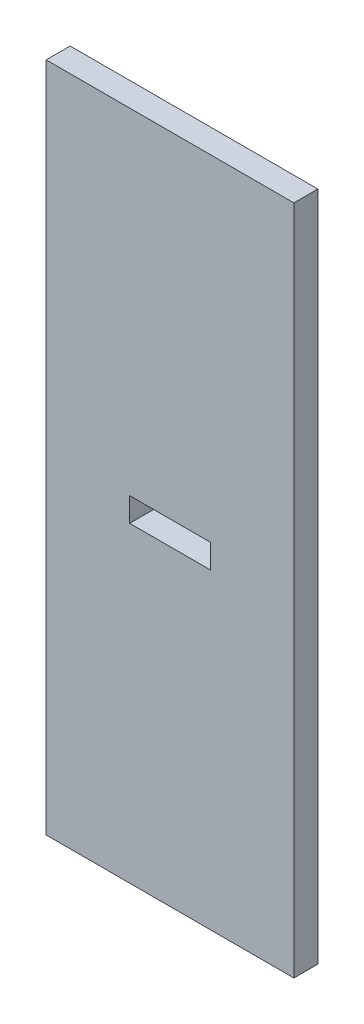
SolidWorks part; units mm, degrees
ref_plane "Plan de face" through (0, 0, 0) normal (0, 0, 1) x (1, 0, 0)
ref_plane "Plan de dessus" through (0, 0, 0) normal (0, 1, 0) x (1, 0, 0)
ref_plane "Plan de droite" through (0, 0, 0) normal (1, 0, 0) x (0, 0, -1)
sketch "Esquisse1" plane through (0, 0, 0) normal (0, 0, 1) x (1, 0, 0)
  line L0 (0, 84) -> (0, 0)
  line L1 (0, 0) -> (31, 0)
  line L3 (0, 84) -> (31, 84)
  line L4 (31, 0) -> (31, 84)
  line L37 (10.45, 42) -> (10.45, 39)
  line L38 (10.45, 42) -> (20.55, 42)
  line L39 (20.55, 42) -> (20.55, 39)
  line L40 (10.45, 39) -> (20.55, 39)
  point P9 (0, 0)
  point P11 (0, 0)
  dimension "D1" = 84
  dimension "D2" = 31
extrude "Boss.-Extru.1" add sketch "Esquisse1" along normal blind 3
